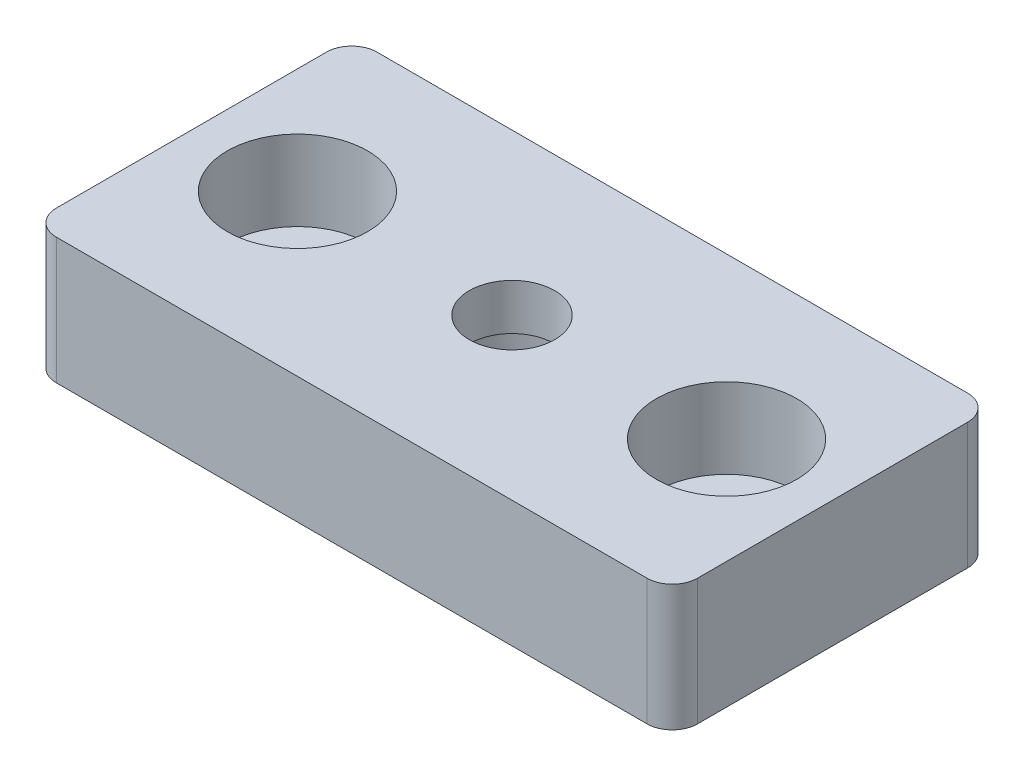
SolidWorks part; units mm, degrees
ref_plane "Front Plane" through (0, 0, 0) normal (0, 0, 1) x (1, 0, 0)
ref_plane "Top Plane" through (0, 0, 0) normal (0, 1, 0) x (1, 0, 0)
ref_plane "Right Plane" through (0, 0, 0) normal (1, 0, 0) x (0, 0, -1)
sketch "Sketch1" plane through (0, 0, 0) normal (0, 1, 0) x (1, 0, 0)
  line L1 (-36.0719, 4.8048) -> (14.7281, 4.8048)
  line L2 (-36.0719, 4.8048) -> (-36.0719, -20.5952)
  line L3 (-36.0719, -20.5952) -> (14.7281, -20.5952)
  line L4 (14.7281, 4.8048) -> (14.7281, -20.5952)
  dimension "D1" = 50.8
  dimension "D2" = 25.4
extrude "Boss-Extrude1" add sketch "Sketch1" along normal blind 10
sketch "Sketch8" plane through (0, 10, 0) normal (0, 1, 0) x (1, 0, 0)
  line L0 (14.7281, 4.8048) -> (-36.0719, 4.8048) construction
  point P0 (-10.6719, -7.8952)
  point P1 (6.3281, -7.8952)
  point P2 (-27.6719, -7.8952)
  point P5 (-10.6719, 4.8048)
  dimension "D1" = 17
  dimension "D2" = 17
  dimension "D3" = 0
hole_wizard "CBORE for 1/4 Socket Head Cap Screw2" positions "Sketch9" profile "Sketch10" counterbore size "1/4" standard "ANSI Inch" end condition through all
sketch "Sketch9" plane through (0, 10, 0) normal (0, 1, 0) x (1, 0, 0)
  point P0 (-27.6719, -7.8952)
  point P3 (6.3281, -7.8952)
sketch "Sketch10" plane through (-27.6719, 10, 7.8952) normal (1, 0, 0) x (0, 0, 1)
  line L0 (0, 0) -> (0, 10)
  line L1 (0, 10) -> (3.3782, 10)
  line L3 (3.3782, 10) -> (3.3782, 6.35)
  line L4 (3.3782, 6.35) -> (5.5562, 6.35)
  line L5 (5.5562, 6.35) -> (5.5562, 0)
  line L7 (5.5562, 0) -> (0, 0)
  line L11 (0, -6.35) -> (0, 107.95) construction
  dimension "Thru Hole Dia." = 6.7564
  dimension "Thru Hole Depth" = 10
  dimension "C'Bore Dia." = 11.1125
  dimension "C'Bore Depth" = 6.35
hole_wizard "CBORE for 1/4 Socket Head Cap Screw3" positions "Sketch11" profile "Sketch12" counterbore size "1/4" standard "ANSI Inch" end condition through all
sketch "Sketch11" plane through (0, 0, 0) normal (0, -1, 0) x (-1, 0, 0)
  point P0 (10.6719, -7.8952)
sketch "Sketch12" plane through (-10.6719, 0, 7.8952) normal (1, 0, 0) x (0, 0, -1)
  line L0 (0, 0) -> (0, 10)
  line L1 (0, 10) -> (3.3782, 10)
  line L3 (3.3782, 10) -> (3.3782, 6.35)
  line L4 (3.3782, 6.35) -> (5.5562, 6.35)
  line L5 (5.5562, 6.35) -> (5.5562, 0)
  line L7 (5.5562, 0) -> (0, 0)
  line L11 (0, -6.35) -> (0, 107.95) construction
  dimension "Thru Hole Dia." = 6.7564
  dimension "Thru Hole Depth" = 10
  dimension "C'Bore Dia." = 11.1125
  dimension "C'Bore Depth" = 6.35
fillet "Fillet2" radius 2 4 edges at (14.7281, 5, -4.8048) (14.7281, 5, 20.5952) (-36.0719, 5, 20.5952) (-36.0719, 5, -4.8048)
equation "\"SlotWidth\"=5"
